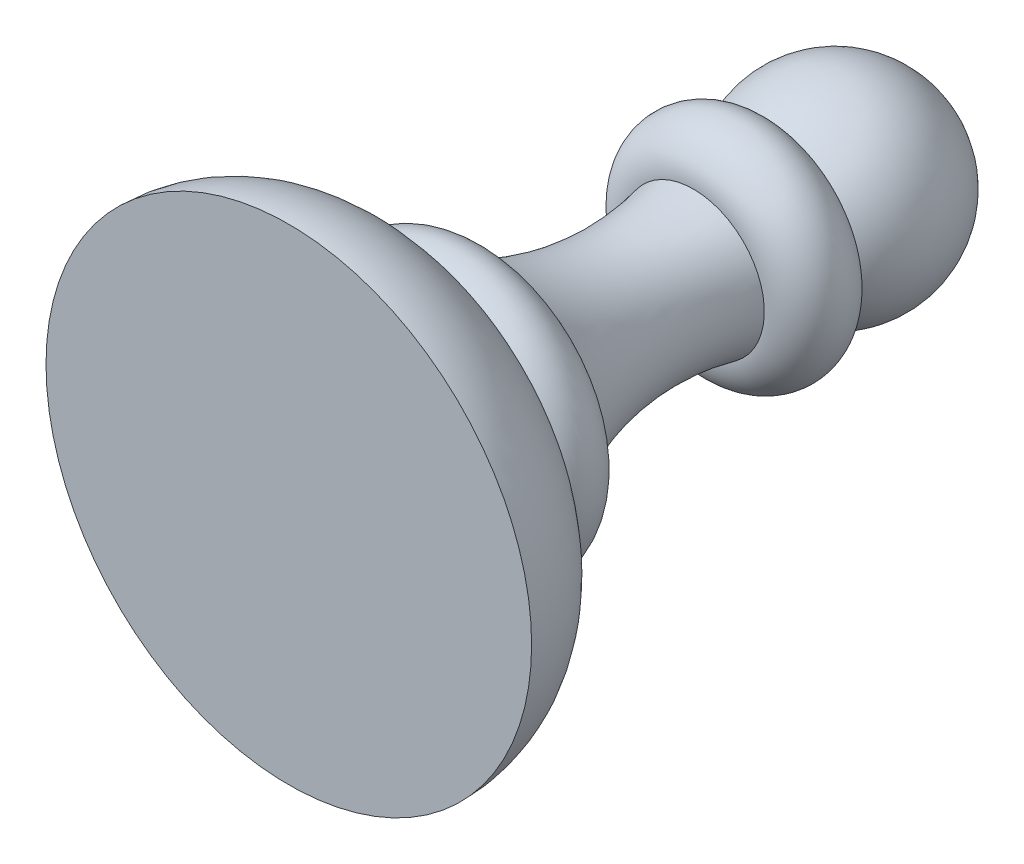
SolidWorks part; units mm, degrees
ref_plane "Front Plane" through (0, 0, 0) normal (0, 0, 1) x (1, 0, 0)
ref_plane "Top Plane" through (0, 0, 0) normal (0, 1, 0) x (1, 0, 0)
ref_plane "Right Plane" through (0, 0, 0) normal (1, 0, 0) x (0, 0, -1)
sketch "Sketch1" plane through (0, 0, 0) normal (0, 1, 0) x (1, 0, 0)
  line L0 (0, 25) -> (0, -135)
  line L1 (-17.5, -25) -> (17.5, -25) construction
  line L2 (-17.5, -15) -> (17.5, -15)
  line L3 (-17.5, -35) -> (17.5, -35)
  line L4 (-25, -95) -> (25, -95) construction
  line L5 (-25, -85) -> (25, -85)
  line L6 (-25, -105) -> (25, -105)
  line L7 (-30, -135) -> (30, -135) construction
  line L8 (-30, -105) -> (30, -105)
  line L9 (-30, -165) -> (30, -165)
  line L10 (0, -135) -> (60, -135)
  circle A0 centre (0, 0) radius 25
  arc A1 (-17.5, -15) -> (-17.5, -35) centre (-17.5, -25) ccw
  arc A2 (17.5, -35) -> (17.5, -15) centre (17.5, -25) ccw
  arc A3 (-25, -85) -> (-25, -105) centre (-25, -95) ccw
  arc A4 (25, -105) -> (25, -85) centre (25, -95) ccw
  arc A7 (17.5, -35) -> (25, -85) centre (85.8037, -50.3169) ccw
  arc A8 (-30, -105) -> (-30, -165) centre (-30, -135) ccw
  arc A9 (30, -165) -> (30, -105) centre (30, -135) ccw
  point P7 (0, -25)
  point P14 (0, -95)
  point P21 (0, -135)
  dimension "D1" = 50
  dimension "D4" = 10
  dimension "D6" = 10
  dimension "D8" = 70
  dimension "D10" = 60
  dimension "D9" = 30
  dimension "D2" = 160
  dimension "D3" = 35
  dimension "D5" = 70
  dimension "D7" = 50
revolve "Revolve1" add sketch "Sketch1" angle 360 about L0
